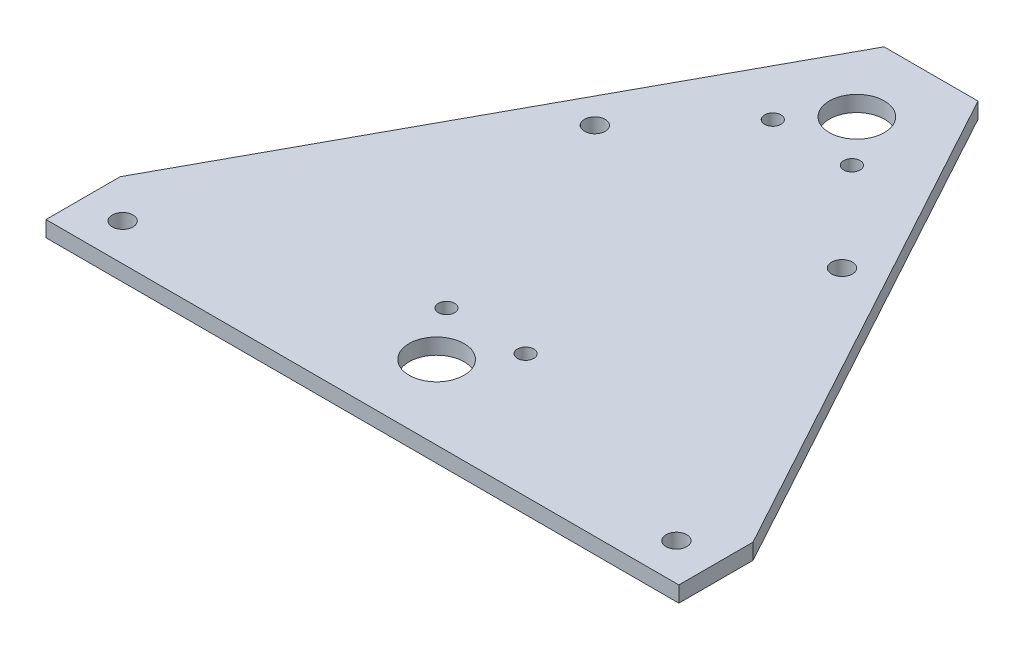
SolidWorks part; units mm, degrees
ref_plane "Front Plane" through (0, 0, 0) normal (1, 0, 0) x (0, 1, 0)
ref_plane "Top Plane" through (0, 0, 0) normal (0, 0, 1) x (0, 1, 0)
ref_plane "Right Plane" through (0, 0, 0) normal (0, 1, 0) x (-1, 0, 0)
sketch "Sketch1" plane through (0, 0, 0) normal (0, 1, 0) x (-1, 0, 0)
  line L0 (-320, 75) -> (320, 75)
  line L1 (-320, 75) -> (-320, 0)
  line L2 (-47.5, -500) -> (47.5, -500)
  line L3 (-320, 0) -> (-47.5, -500)
  line L4 (0, 0) -> (0, -643.6385) construction
  line L5 (320, 0) -> (47.5, -500)
  line L6 (320, 75) -> (320, 0)
  circle A0 centre (0, 0) radius 27.8
  circle A1 centre (0, -425) radius 27.8
  circle A2 centre (-40, -50) radius 8.3
  circle A3 centre (40, -50) radius 8.3
  circle A4 centre (-40, -380) radius 8.3
  circle A5 centre (40, -380) radius 8.3
  circle A6 centre (-280, 37.5) radius 10.5
  circle A7 centre (280, 37.5) radius 10.5
  circle A8 centre (-125, -285) radius 10.5
  circle A9 centre (125, -285) radius 10.5
  point P5 (0, 75)
  point P9 (0, -500)
  point P22 (-320, 37.5)
  dimension "D1" = 55.6
  dimension "D6" = 75
  dimension "D7" = 16.6
  dimension "D11" = 21
  dimension "D13" = 250
  dimension "D2" = 640
  dimension "D3" = 75
  dimension "D4" = 95
  dimension "D5" = 575
  dimension "D8" = 80
  dimension "D9" = 375
  dimension "D10" = 45
  dimension "D12" = 560
  dimension "D14" = 140
extrude "Boss-Extrude1" add sketch "Sketch1" along normal blind 16
